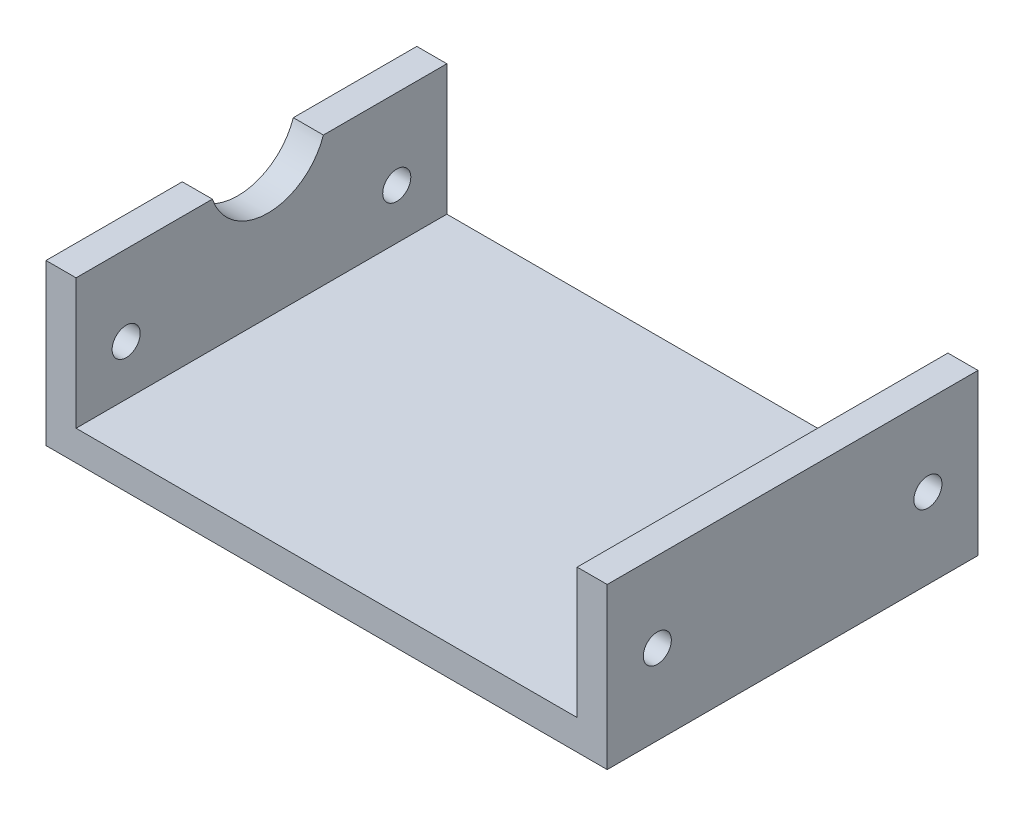
SolidWorks part; units mm, degrees
ref_plane "Plano frontal" through (0, 0, 0) normal (0, 0, 1) x (1, 0, 0)
ref_plane "Plano superior" through (0, 0, 0) normal (0, 1, 0) x (1, 0, 0)
ref_plane "Plano direito" through (0, 0, 0) normal (1, 0, 0) x (0, 0, -1)
sketch "Esboço1" plane through (0, 0, 0) normal (0, 1, 0) x (1, 0, 0)
  line L1 (-9.3853, 22.1739) -> (46.6147, 22.1739)
  line L2 (-9.3853, 22.1739) -> (-9.3853, 59.1739)
  line L3 (-9.3853, 59.1739) -> (46.6147, 59.1739)
  line L4 (46.6147, 22.1739) -> (46.6147, 59.1739)
extrude "Ressalto-extrusão1" add sketch "Esboço1" along normal blind 3
sketch "Esboço10" plane through (0, 3, 0) normal (0, 1, 0) x (1, 0, 0)
  line L0 (-9.3853, 22.1739) -> (46.6147, 22.1739) construction
  line L1 (-9.3853, 59.1739) -> (-6.3853, 59.1739)
  line L2 (-9.3853, 59.1739) -> (-9.3853, 22.1739)
  line L3 (-9.3853, 22.1739) -> (-6.3853, 22.1739)
  line L4 (-6.3853, 59.1739) -> (-6.3853, 22.1739)
extrude "Ressalto-extrusão2" add sketch "Esboço10" along normal blind 13
sketch "Esboço13" plane through (0, 3, 0) normal (0, 1, 0) x (1, 0, 0)
  line L0 (-6.3853, 22.1739) -> (46.6147, 22.1739) construction
  line L1 (46.6147, 59.1739) -> (43.6147, 59.1739)
  line L2 (46.6147, 59.1739) -> (46.6147, 22.1739)
  line L3 (46.6147, 22.1739) -> (43.6147, 22.1739)
  line L4 (43.6147, 59.1739) -> (43.6147, 22.1739)
extrude "Ressalto-extrusão3" add sketch "Esboço13" along normal blind 13
sketch "Esboço14" plane through (-9.3853, 0, 0) normal (-1, 0, 0) x (0, 0, 1)
  circle A0 centre (-41.3141, 17.8592) radius 5.8427
sketch "Esboço15" plane through (-9.3853, 0, 0) normal (-1, 0, 0) x (0, 0, 1)
  line L0 (-22.1739, 16) -> (-22.1739, 0)
  circle A0 centre (-54.1739, 8) radius 1.4
  circle A1 centre (-41.3141, 17.8592) radius 5.8427
  circle A2 centre (-27.1739, 8) radius 1.4
  dimension "D1" = 2.8
  dimension "D2" = 2.8
extrude "Corte-extrusão1" cut sketch "Esboço14" against normal blind 30 contours A0
extrude "Corte-extrusão2" cut sketch "Esboço15" against normal blind 60 contours A2
sketch "Esboço16" plane through (-9.3853, 0, 0) normal (-1, 0, 0) x (0, 0, 1)
sketch "Esboço17" plane through (-9.3853, 0, 0) normal (-1, 0, 0) x (0, 0, 1)
  line L0 (-27.1739, 8) -> (-22.1739, 8)
  line L1 (-22.1739, 16) -> (-22.1739, 0) construction
  circle A0 centre (-54.1739, 8) radius 1.4
  dimension "D1" = 2.8
extrude "Corte-extrusão3" cut sketch "Esboço17" against normal blind 60 contours A0
